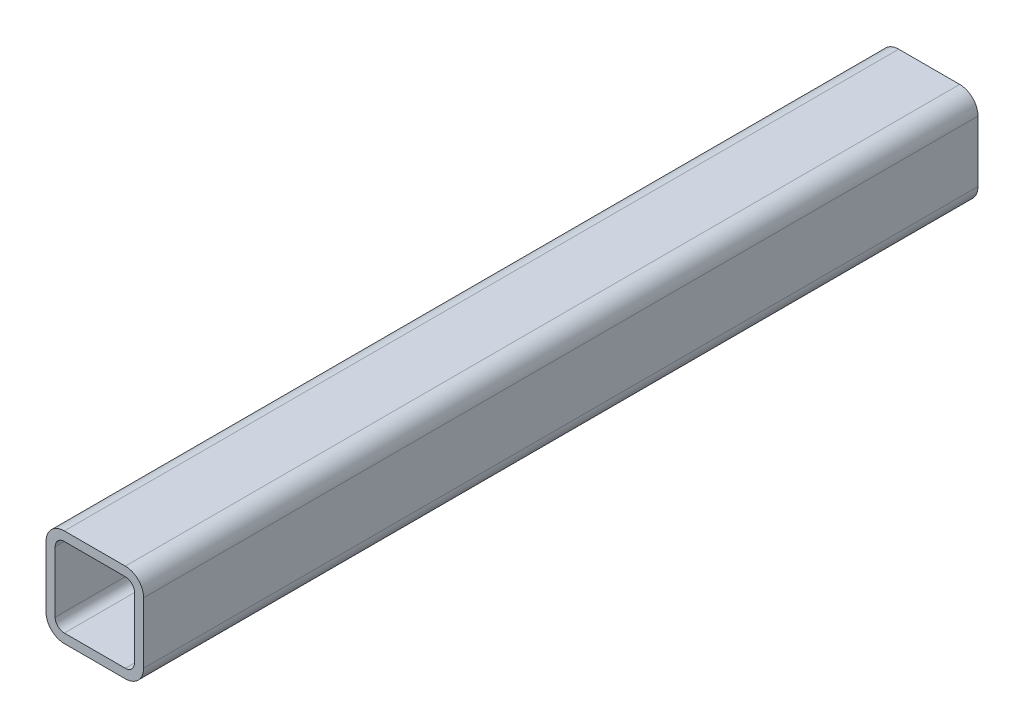
SolidWorks part; units mm, degrees
ref_plane "Płaszczyzna przednia" through (0, 0, 0) normal (0, 0, 1) x (1, 0, 0)
ref_plane "Płaszczyzna górna" through (0, 0, 0) normal (0, 1, 0) x (1, 0, 0)
ref_plane "Płaszczyzna prawa" through (0, 0, 0) normal (1, 0, 0) x (0, 0, -1)
sketch "Szkic1" plane through (0, 0, 0) normal (0, 0, 1) x (1, 0, 0)
  line L1 (9.53, 0) -> (41.27, 0)
  line L2 (0, 9.53) -> (0, 41.27)
  line L3 (9.53, 50.8) -> (41.27, 50.8)
  line L4 (50.8, 9.53) -> (50.8, 41.27)
  line L5 (9.52, 46.04) -> (41.28, 46.04)
  line L6 (4.76, 41.28) -> (4.76, 9.52)
  line L7 (9.52, 4.76) -> (41.28, 4.76)
  line L8 (46.04, 41.28) -> (46.04, 9.52)
  arc A0 (4.76, 9.52) -> (9.52, 4.76) centre (9.52, 9.52) ccw
  arc A1 (41.28, 4.76) -> (46.04, 9.52) centre (41.28, 9.52) ccw
  arc A2 (46.04, 41.28) -> (41.28, 46.04) centre (41.28, 41.28) ccw
  arc A3 (4.76, 41.28) -> (9.52, 46.04) centre (9.52, 41.28) cw
  arc A4 (41.27, 50.8) -> (50.8, 41.27) centre (41.27, 41.27) cw
  arc A5 (50.8, 9.53) -> (41.27, 0) centre (41.27, 9.53) cw
  arc A6 (9.53, 0) -> (0, 9.53) centre (9.53, 9.53) cw
  arc A7 (0, 41.27) -> (9.53, 50.8) centre (9.53, 41.27) cw
  dimension "D7" = 4.76
  dimension "D8" = 9.53
  dimension "D1" = 50.8
  dimension "D2" = 50.8
  dimension "D3" = 41.28
  dimension "D4" = 41.28
  dimension "D5" = 4.76
  dimension "D6" = 4.76
extrude "Dodanie-wyciągnięcie1" add sketch "Szkic1" along normal blind 434.2
